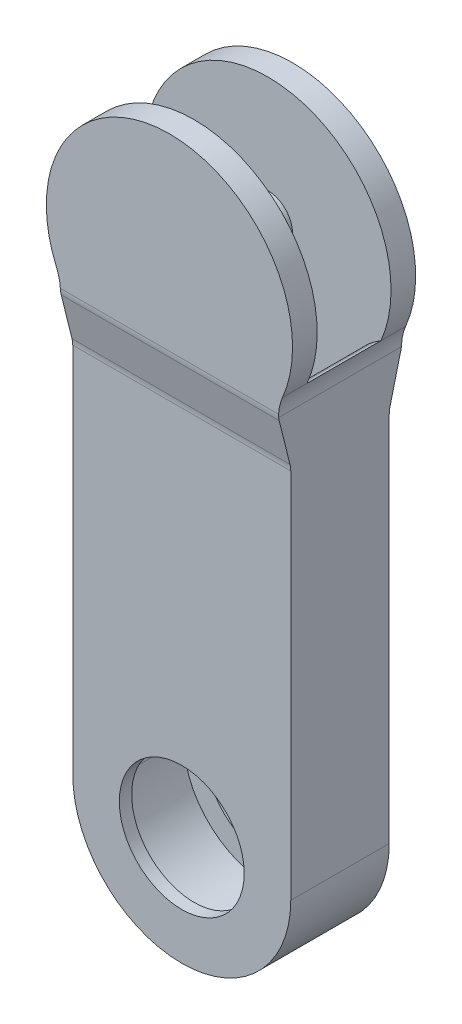
SolidWorks part; units mm, degrees
ref_plane "Plan de face" through (0, 0, 0) normal (0, 0, 1) x (1, 0, 0)
ref_plane "Plan de dessus" through (0, 0, 0) normal (0, 1, 0) x (1, 0, 0)
ref_plane "Plan de droite" through (0, 0, 0) normal (1, 0, 0) x (0, 0, -1)
sketch "Esquisse1" plane through (0, 0, 0) normal (0, 0, 1) x (1, 0, 0)
  line L1 (44.2731, -200) -> (44.2731, -27.7303)
  line L2 (-44.2731, -200) -> (-44.2731, -27.7303)
  arc A0 (45.9094, -19.8073) -> (-45.9094, -19.8073) centre (0, 0) ccw
  arc A1 (-44.2731, -200) -> (44.2731, -200) centre (0, -200) ccw
  arc A2 (-44.2731, -27.7303) -> (-45.9094, -19.8073) centre (-64.2731, -27.7303) ccw
  arc A3 (44.2731, -27.7303) -> (45.9094, -19.8073) centre (64.2731, -27.7303) cw
  dimension "D1" = 20
  dimension "D3" = 50
  dimension "D2" = 200
extrude "Boss.-Extru.1" add sketch "Esquisse1" along normal mid plane 50
sketch "Esquisse3" plane through (0, 0, 0) normal (0, 0, 1) x (1, 0, 0)
  line L0 (-34.2731, -27.7303) -> (-34.2731, -200) construction
  line L2 (34.2731, -200) -> (34.2731, -38.3085)
  line L3 (34.2731, -200) -> (34.2731, -27.7303) construction
  line L5 (-34.2731, -38.3085) -> (-34.2731, -200)
  line L12 (-43.0169, -21.7768) -> (-45.9094, -19.8073)
  line L13 (45.9094, -19.8073) -> (43.0169, -21.7768)
  line L14 (-44.2731, -27.7303) -> (-44.2731, -200) construction
  line L15 (44.2731, -200) -> (44.2731, -27.7303) construction
  arc A0 (-34.2731, -38.3085) -> (-43.0169, -21.7768) centre (-54.2731, -38.3085) ccw
  arc A1 (34.2731, -38.3085) -> (43.0169, -21.7768) centre (54.2731, -38.3085) cw
  arc A2 (45.9094, -19.8073) -> (-45.9094, -19.8073) centre (0, 0) ccw
  arc A10 (34.2731, -200) -> (-34.2731, -200) centre (0, -200) cw
  arc A11 (34.2731, -27.7303) -> (36.7275, -15.8459) centre (64.2731, -27.7303) cw construction
  arc A12 (36.7275, -15.8459) -> (-36.7275, -15.8459) centre (0, 0) ccw construction
  arc A13 (-34.2731, -27.7303) -> (-36.7275, -15.8459) centre (-64.2731, -27.7303) ccw construction
  arc A14 (-44.2731, -27.7303) -> (-45.9094, -19.8073) centre (-64.2731, -27.7303) ccw construction
  arc A15 (44.2731, -27.7303) -> (45.9094, -19.8073) centre (64.2731, -27.7303) cw construction
  arc A16 (44.2731, -200) -> (-44.2731, -200) centre (0, -200) cw construction
  dimension "D1" = 20
  dimension "D2" = 10
extrude "Enlèv. mat.-Extru.1" cut sketch "Esquisse3" against normal mid plane 30
sketch "Esquisse4" plane through (0, 0, 25) normal (0, 0, 1) x (1, 0, 0)
  circle A1 centre (0, -200) radius 25.355
  dimension "D1" = 50.71
extrude "Enlèv. mat.-Extru.2" cut sketch "Esquisse4" against normal through all
sketch "Esquisse5" plane through (0, 0, -15) normal (0, 0, 1) x (1, 0, 0)
  circle A0 centre (0, 0) radius 10
extrude "Boss.-Extru.2" add sketch "Esquisse5" along normal up to surface (30 mm away) up to face at (25.355, -200, 15)
sketch "Esquisse6" plane through (-44.2731, 0, 0) normal (-1, 0, 0) x (0, 0, 1)
  line L0 (-25, -27.7303) -> (-20, -47.7303)
  line L1 (-25, -248.8509) -> (-25, -27.7303)
  line L4 (-20, -47.7303) -> (-20, -248.8509)
  line L5 (-20, -248.8509) -> (-25, -248.8509)
  line L6 (20, -248.8509) -> (25, -248.8509)
  line L7 (20, -47.7303) -> (20, -248.8509)
  line L8 (25, -248.8509) -> (25, -27.7303)
  line L9 (25, -27.7303) -> (20, -47.7303)
extrude "Enlèv. mat.-Extru.3" cut sketch "Esquisse6" against normal through all
fillet "Congé1" radius 10 4 edges at (0, -47.7303, 20) (0, -27.7303, 25) (0, -47.7303, -20) (0, -27.7303, -25)
